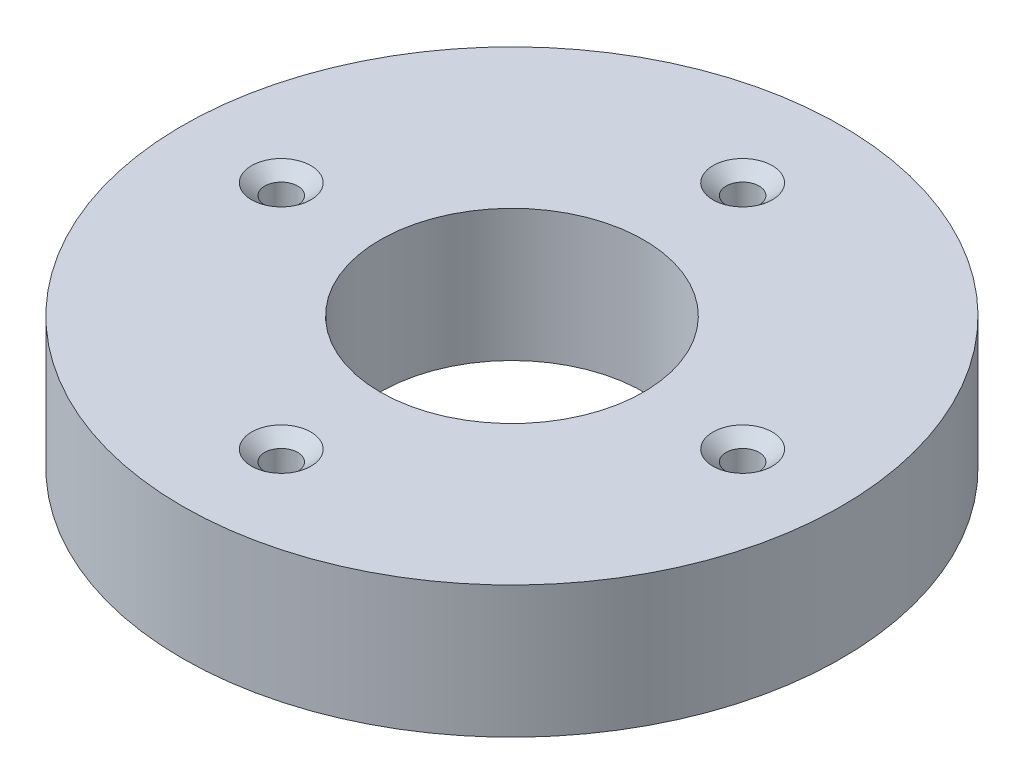
SolidWorks part; units mm, degrees
ref_plane "Front Plane" through (0, 0, 0) normal (0, 0, 1) x (1, 0, 0)
ref_plane "Top Plane" through (0, 0, 0) normal (0, 1, 0) x (1, 0, 0)
ref_plane "Right Plane" through (0, 0, 0) normal (1, 0, 0) x (0, 0, -1)
sketch "Sketch1" plane through (0, 0, 0) normal (0, 1, 0) x (1, 0, 0)
  circle A0 centre (0, 0) radius 15.875
  dimension "D1" = 31.75
extrude "Boss-Extrude1" add sketch "Sketch1" along normal blind 6.35
sketch "Sketch2" plane through (0, 6.35, 0) normal (0, 1, 0) x (1, 0, 0)
  circle A0 centre (0, 0) radius 6.35
  dimension "D1" = 12.7
extrude "Cut-Extrude1" cut sketch "Sketch2" against normal through all
sketch "Sketch5" plane through (0, 6.35, 0) normal (0, 1, 0) x (1, 0, 0)
  line L0 (0, 0) -> (0, 11.1125)
  line L1 (0, 0) -> (11.1125, 0)
  dimension "D1" = 11.1125
  dimension "D2" = 11.1125
hole_wizard "1/16 (0.0625) Diameter Hole1" positions "Sketch6" profile "Sketch7" hole size "1/16" standard "ANSI Inch" end condition through all
sketch "Sketch6" plane through (0, 6.35, 0) normal (0, 1, 0) x (1, 0, 0)
  point P0 (0, 11.1125)
sketch "Sketch7" plane through (0, 6.35, -11.1125) normal (1, 0, 0) x (0, 0, 1)
  line L0 (0, 0) -> (0, 6.35)
  line L1 (0, 6.35) -> (0.7937, 6.35)
  line L2 (0.7937, 6.35) -> (0.7937, 0.5328)
  line L3 (0.7937, 0.5328) -> (1.4287, 0)
  line L5 (1.4287, 0) -> (0, 0)
  line L6 (-0.7937, 0.5328) -> (-1.4287, 0) construction
  line L11 (0, -6.35) -> (0, 107.95) construction
  dimension "Thru Hole Dia." = 1.5875
  dimension "Thru Hole Depth" = 6.35
  dimension "Near C'Sink Dia." = 2.8575
  dimension "Near C'Sink Angle" = 100
pattern_circular "CirPattern1" count 2 every 180 about axis through (0, 0, 0) along (0, 1, 0) of "1/16 (0.0625) Diameter Hole1"
hole_wizard "1/16 (0.0625) Diameter Hole2" positions "Sketch9" profile "Sketch10" hole size "1/16" standard "ANSI Inch"
sketch "Sketch9" plane through (0, 6.35, 0) normal (0, 1, 0) x (1, 0, 0)
  point P0 (11.1125, 0)
sketch "Sketch10" plane through (11.1125, 6.35, 0) normal (1, 0, 0) x (0, 0, 1)
  line L0 (0, 0) -> (0, 4.2869)
  line L1 (0, 4.2869) -> (0.7937, 3.81)
  line L2 (0.7937, 3.81) -> (0.7937, 0.5328)
  line L3 (0.7937, 0.5328) -> (1.4287, 0)
  line L5 (1.4287, 0) -> (0, 0)
  line L6 (-0.7937, 0.5328) -> (-1.4287, 0) construction
  line L10 (0, 4.2869) -> (-0.7937, 3.81) construction
  line L11 (0, -6.35) -> (0, 107.95) construction
  dimension "Hole Dia." = 1.5875
  dimension "Hole Depth" = 3.81
  dimension "Near C'Sink Dia." = 2.8575
  dimension "Near C'Sink Angle" = 100
  dimension "Drill Angle" = 118
pattern_circular "CirPattern2" count 2 every 180 about axis through (0, 0, 0) along (0, 1, 0) of "1/16 (0.0625) Diameter Hole2"
